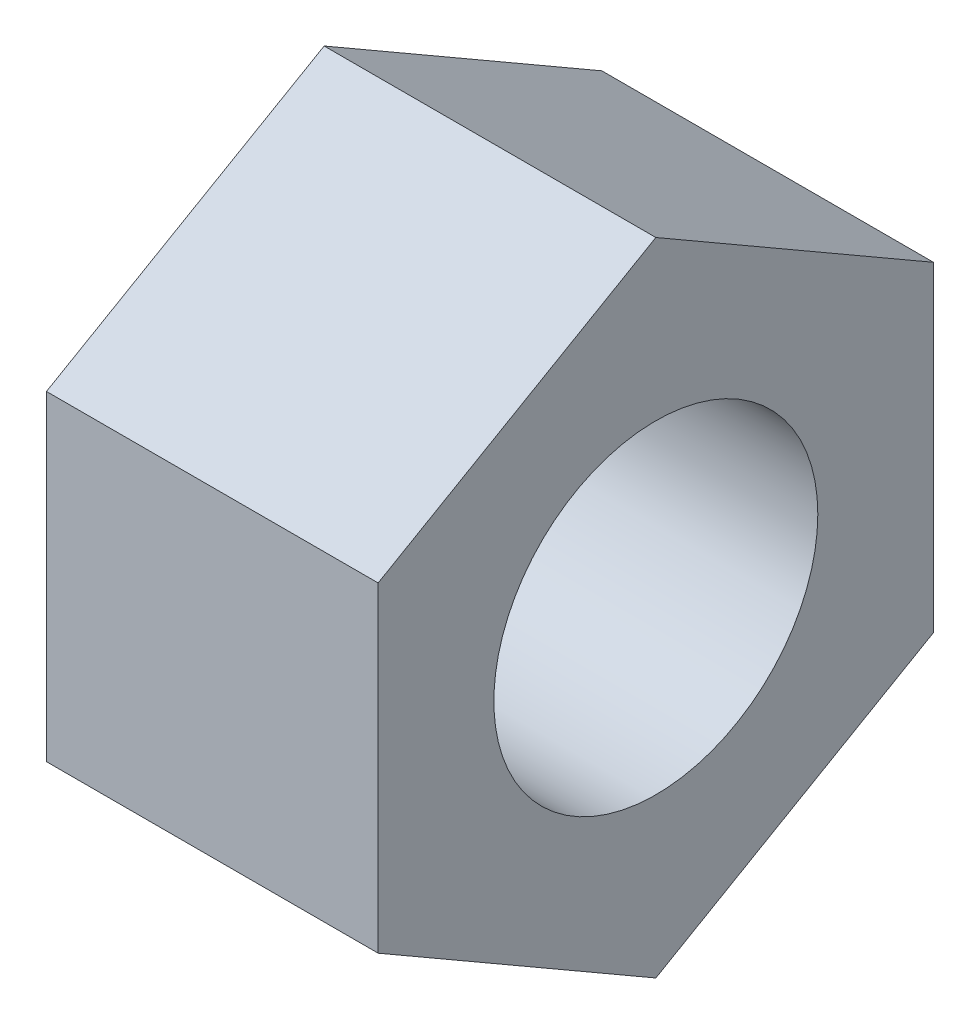
SolidWorks part; units mm, degrees
material "Alloy Steel"
ref_plane "Front Plane" through (0, 0, 0) normal (0, 0, 1) x (1, 0, 0)
ref_plane "Top Plane" through (0, 0, 0) normal (0, 1, 0) x (1, 0, 0)
ref_plane "Right Plane" through (0, 0, 0) normal (1, 0, 0) x (0, 0, -1)
other "PropertyManager"
sketch "BaseNutSketch" plane through (0, 0, 0) normal (1, 0, 0) x (0, -1, 0)
  line L1 (10.3923, 18) -> (-10.3923, 18)
  line L2 (-10.3923, 18) -> (-20.7846, 0)
  line L3 (-20.7846, 0) -> (-10.3923, -18)
  line L4 (-10.3923, -18) -> (10.3923, -18)
  line L5 (10.3923, -18) -> (20.7846, 0)
  line L6 (20.7846, 0) -> (10.3923, 18)
  circle A0 centre (0, 0) radius 18 construction
  circle A1 centre (0, 0) radius 10.5
  dimension "Width_flats" = 36
  dimension "Tap_drill" = 21
extrude "BaseNut" add sketch "BaseNutSketch" along normal blind 21.5
cosmetic thread "Thread" parameters "Thread_major"=24
other "Freeze***"
